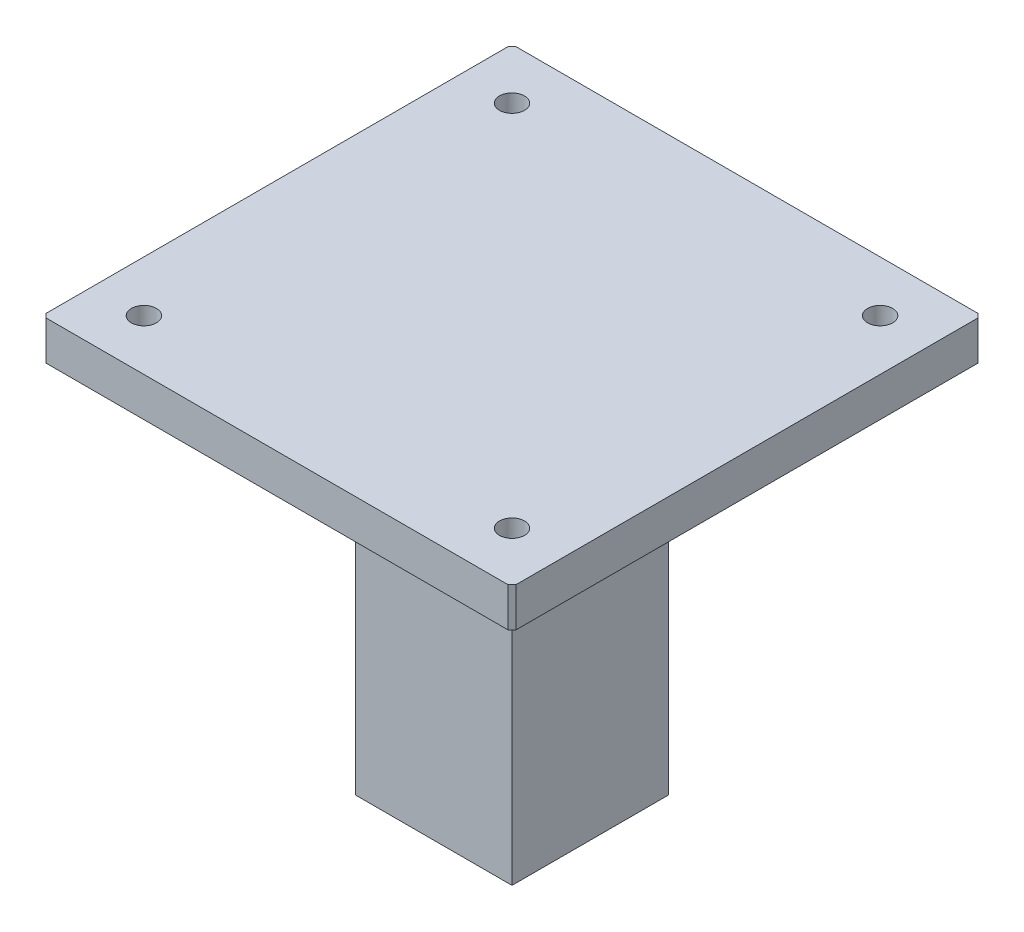
SolidWorks part; units mm, degrees
ref_plane "Ebene vorne" through (0, 0, 0) normal (0, 0, 1) x (1, 0, 0)
ref_plane "Ebene oben" through (0, 0, 0) normal (0, 1, 0) x (1, 0, 0)
ref_plane "Ebene rechts" through (0, 0, 0) normal (1, 0, 0) x (0, 0, -1)
sketch "Skizze1" plane through (0, 0, 0) normal (0, 1, 0) x (1, 0, 0)
  line L1 (0, 0) -> (50, 0) construction
  line L2 (0, 0) -> (0, 60) construction
  line L3 (0, 60) -> (50, 60) construction
  line L4 (50, 0) -> (50, 60) construction
  line L5 (10, 55) -> (40, 55) construction
  line L6 (10, 55) -> (10, 5) construction
  line L7 (10, 5) -> (40, 5) construction
  line L8 (40, 55) -> (40, 5) construction
  line L9 (-5, 0) -> (55, 0)
  line L10 (-5, 0) -> (-5, 60)
  line L11 (-5, 60) -> (55, 60)
  line L12 (55, 0) -> (55, 60)
  point P9 (10, 30)
  point P10 (0, 30)
  point P11 (25, 55)
  point P12 (25, 60)
  point P13 (25, 30)
  point P19 (55, 30)
  point P20 (25, 60)
  dimension "D5" = 60
  dimension "D1" = 50
  dimension "D2" = 60
  dimension "D3" = 10
  dimension "D4" = 5
extrude "Aufsatz-Linear austragen1" add sketch "Skizze1" along normal blind 5
sketch "Skizze7" plane through (0, 5, 0) normal (0, 1, 0) x (1, 0, 0)
  line L1 (5, 10) -> (45, 10) construction
  line L2 (5, 10) -> (5, 50) construction
  line L3 (5, 50) -> (45, 50) construction
  line L4 (45, 10) -> (45, 50) construction
  line L5 (5, 10) -> (45, 50) construction
  line L6 (5, 50) -> (45, 10) construction
  line L7 (1.5, 53.5) -> (1.5, 6.5) construction
  line L8 (48.5, 53.5) -> (48.5, 6.5) construction
  line L10 (48.5, 6.5) -> (1.5, 6.5) construction
  line L11 (1.5, 53.5) -> (48.5, 53.5) construction
  circle A0 centre (1.5, 53.5) radius 1.6
  circle A1 centre (48.5, 53.5) radius 1.6
  circle A2 centre (48.5, 6.5) radius 1.6
  circle A3 centre (1.5, 6.5) radius 1.6
  point P0 (25, 30)
  point P5 (25, 53.5)
  point P10 (48.5, 30)
  dimension "D4" = 3.2
  dimension "D1" = 47
  dimension "D2" = 40
  dimension "D3" = 47
extrude "Schnitt-Linear austragen1" cut sketch "Skizze7" against normal blind 10 contours A2 | A1 | A0 | A3
chamfer "Fase1" distance 0.5 angle 45 4 edges at (-5, 2.5, 0) (55, 2.5, 0) (55, 2.5, -60) (-5, 2.5, -60)
sketch "Skizze8" plane through (0, 0, 0) normal (0, -1, 0) x (1, 0, 0)
  line L0 (55, -30) -> (35, -30) construction
  line L1 (15, -20) -> (35, -20)
  line L2 (15, -20) -> (15, -40)
  line L3 (15, -40) -> (35, -40)
  line L4 (35, -20) -> (35, -40)
  line L5 (55, -0.5) -> (55, -59.5) construction
  line L6 (25, -20) -> (25, 0) construction
  line L7 (-4.5, 0) -> (54.5, 0) construction
  dimension "D1" = 20
  dimension "D2" = 20
extrude "Aufsatz-Linear austragen2" add sketch "Skizze8" along normal blind 48
